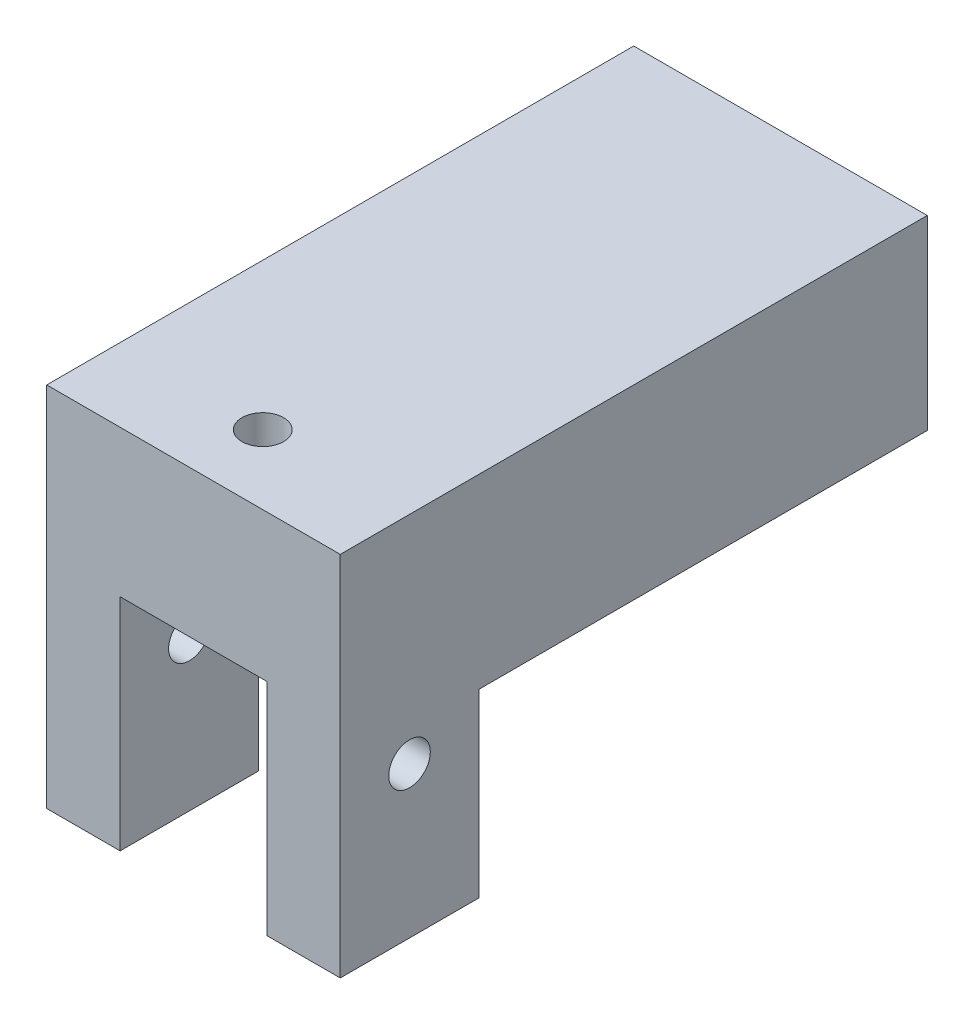
SolidWorks part; units mm, degrees
ref_plane "Front Plane" through (0, 0, 0) normal (0, 0, 1) x (1, 0, 0)
ref_plane "Top Plane" through (0, 0, 0) normal (0, 1, 0) x (1, 0, 0)
ref_plane "Right Plane" through (0, 0, 0) normal (1, 0, 0) x (0, 0, -1)
sketch "Sketch1" plane through (0, 0, 0) normal (1, 0, 0) x (0, 0, -1)
  line L0 (0, 0) -> (0, 31.75)
  line L1 (0, 31.75) -> (50.8, 31.75)
  line L2 (50.8, 31.75) -> (50.8, 15.6337)
  line L4 (11.9888, 15.6337) -> (11.9888, 0)
  line L5 (11.9888, 0) -> (0, 0)
  line L7 (11.9888, 15.6337) -> (50.8, 15.6337)
  line L8 (0, 12.7) -> (11.9888, 12.7) construction
  line L9 (0, 15.1257) -> (0, 10.2743) construction
  line L10 (0, 15.1257) -> (50.8, 15.1257) construction
  line L11 (50.8, 15.1257) -> (50.8, 10.2743) construction
  line L12 (50.8, 10.2743) -> (0, 10.2743) construction
  point P3 (0, 0)
  point P9 (0, 12.7)
  dimension "D1" = 11.9888
  dimension "D2" = 12.7
  dimension "D4" = 50.8
  dimension "D6" = 0.508
  dimension "D7" = 31.75
  dimension "D8" = 4.8514
extrude "Boss-Extrude1" add sketch "Sketch1" along normal blind 25.4
sketch "Sketch2" plane through (0, 0, 0) normal (0, 0, 1) x (1, 0, 0)
  line L0 (25.4, 0) -> (0, 0) construction
  line L1 (6.35, 19.05) -> (19.05, 19.05)
  line L2 (6.35, 19.05) -> (6.35, 0)
  line L3 (6.35, 0) -> (19.05, 0)
  line L4 (19.05, 19.05) -> (19.05, 0)
  line L5 (6.35, 19.05) -> (19.05, 0) construction
  line L6 (6.35, 0) -> (19.05, 19.05) construction
  line L9 (6.35, 12.7) -> (19.05, 12.7) construction
  point P0 (12.7, 9.525)
  point P8 (12.7, 0)
  dimension "D1" = 12.7
  dimension "D2" = 12.7
  dimension "D3" = 6.35
extrude "Cut-Extrude1" cut sketch "Sketch2" against normal up to surface (11.9888 mm away) up to face at (12.7, 7.8168, -11.9888)
hole_wizard "M3 Clearance Hole1" positions "Sketch3" profile "Sketch4" hole size "M3" standard "ANSI Metric" end condition through all
sketch "Sketch3" plane through (25.4, 0, 0) normal (1, 0, 0) x (0, 0, -1)
  line L0 (11.9888, 19.05) -> (0, 19.05) construction
  line L1 (0, 31.75) -> (0, 0) construction
  point P0 (5.9944, 13.0556)
  dimension "D1" = 5.9944
  dimension "D2" = 5.9944
sketch "Sketch4" plane through (25.4, 13.0556, -5.9944) normal (0, 1, 0) x (0, 0, -1)
  line L0 (0, 0) -> (0, 25.4)
  line L1 (0, 25.4) -> (1.8, 25.4)
  line L2 (1.8, 25.4) -> (1.8, 0)
  line L5 (1.8, 0) -> (0, 0)
  line L11 (0, -6.35) -> (0, 107.95) construction
  dimension "Thru Hole Dia." = 3.6
  dimension "Thru Hole Depth" = 25.4
hole_wizard "M3 Clearance Hole2" positions "Sketch5" profile "Sketch6" hole size "M3" standard "ANSI Metric" end condition through all
sketch "Sketch5" plane through (0, 31.75, 0) normal (0, 1, 0) x (1, 0, 0)
  line L0 (25.4, 0) -> (0, 0) construction
  line L1 (25.4, 50.8) -> (25.4, 0) construction
  point P0 (12.7, 5.9944)
  dimension "D1" = 5.9944
  dimension "D2" = 12.7
sketch "Sketch6" plane through (12.7, 31.75, -5.9944) normal (1, 0, 0) x (0, 0, 1)
  line L0 (0, 0) -> (0, 31.75)
  line L1 (0, 31.75) -> (1.8, 31.75)
  line L2 (1.8, 31.75) -> (1.8, 0)
  line L5 (1.8, 0) -> (0, 0)
  line L11 (0, -6.35) -> (0, 107.95) construction
  dimension "Thru Hole Dia." = 3.6
  dimension "Thru Hole Depth" = 31.75
